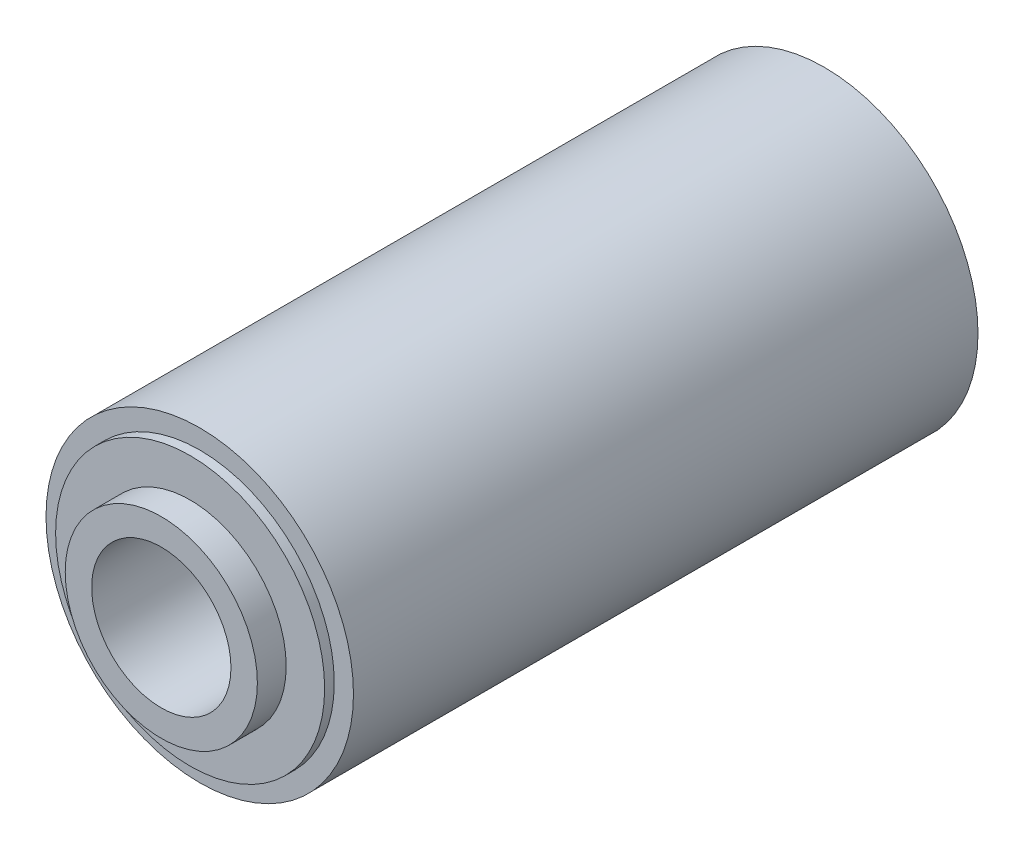
SolidWorks part; units mm, degrees
ref_plane "前视基准面" through (0, 0, 0) normal (0, 0, 1) x (1, 0, 0)
ref_plane "上视基准面" through (0, 0, 0) normal (0, 1, 0) x (1, 0, 0)
ref_plane "右视基准面" through (0, 0, 0) normal (1, 0, 0) x (0, 0, -1)
other "Configuration Table"
sketch "草图1" plane through (0, 0, 0) normal (0, 0, 1) x (1, 0, 0)
  circle A0 centre (0, 0) radius 7.25
  circle A1 centre (0, 0) radius 10
  dimension "D1" = 14.5
  dimension "D2" = 20
extrude "内金属层" add sketch "草图1" along normal blind 73 contours A1 A0
sketch "草图2" plane through (0, 0, 73) normal (0, 0, 1) x (1, 0, 0)
  circle A0 centre (0, 0) radius 14
  circle A1 centre (0, 0) radius 10 construction
  circle M2 centre (0, 0) radius 10
  dimension "D1" = 4
extrude "橡胶层" add sketch "草图2" against normal blind 67 from offset 3 separate body contours A0 M2 offset against normal yes
sketch "草图3" plane through (0, 0, 70) normal (0, 0, 1) x (1, 0, 0)
  circle A0 centre (0, 0) radius 16
  circle M2 centre (0, 0) radius 14
  dimension "D1" = 32
extrude "外金属层" add sketch "草图3" against normal blind 65 from offset 1 separate body contours A0 M2
equation "\"内套内孔\" = 14.5"
equation "\"内套外径\" = 20"
equation "\"橡胶层厚\" = 4"
equation "\"外套外径\" = 32"
equation "\"衬套外层长\" = 65"
equation "\"内层端部伸出量\" = 4"
equation "\"橡胶端部伸出量\" = 1"
equation "\"内套壁厚\"= (\"内套外径\" - \"内套内孔\") / 2"
equation "\"橡胶内径\"= \"内套外径\""
equation "\"橡胶外径\" = \"内套外径\" + 2 * \"橡胶层厚\""
equation "\"外套内径\" = \"橡胶外径\""
equation "\"外套壁厚\"= (\"外套外径\" - \"外套内径\") / 2"
equation "\"外套长度\"= \"衬套外层长\""
equation "\"橡胶长度\" = \"衬套外层长\" + 2 * \"橡胶端部伸出量\""
equation "\"内套长度\" = \"衬套外层长\" + 2 * \"内层端部伸出量\""
equation "\"螺栓公称直径\" = 14"
equation "\"螺栓单边间隙\"= (\"内套内孔\" - \"螺栓公称直径\") / 2"
equation "\"螺栓孔径比\"= \"内套内孔\" / \"螺栓公称直径\""
equation "\"D1@草图1\"=\"内套内孔\""
equation "\"D2@草图1\"=\"内套外径\""
equation "\"D1@内金属层\"=\"内套长度\""
equation "\"D1@草图2\"=\"橡胶层厚\""
equation "\"D19@橡胶层\"=\"内层端部伸出量\"-\"橡胶端部伸出量\""
equation "\"D1@橡胶层\" = \"橡胶长度\""
equation "\"D1@草图3\"=\"外套外径\""
equation "\"D19@外金属层\"=\"橡胶端部伸出量\""
equation "\"D1@外金属层\"=\"衬套外层长\""
